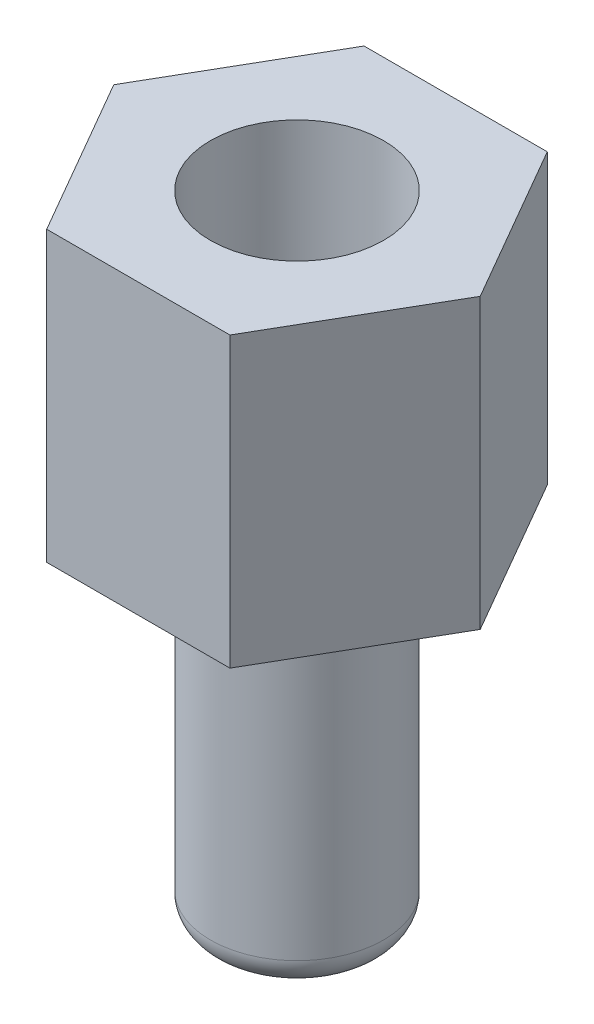
SolidWorks part; units mm, degrees
ref_plane "Front Plane" through (0, 0, 0) normal (0, 0, 1) x (1, 0, 0)
ref_plane "Top Plane" through (0, 0, 0) normal (0, 1, 0) x (1, 0, 0)
ref_plane "Right Plane" through (0, 0, 0) normal (1, 0, 0) x (0, 0, -1)
sketch "Sketch1" plane through (0, 0, 0) normal (0, 1, 0) x (1, 0, 0)
  line L1 (3.1754, 0) -> (1.5877, 2.75)
  line L2 (1.5877, 2.75) -> (-1.5877, 2.75)
  line L3 (-1.5877, 2.75) -> (-3.1754, 0)
  line L4 (-3.1754, 0) -> (-1.5877, -2.75)
  line L5 (-1.5877, -2.75) -> (1.5877, -2.75)
  line L6 (1.5877, -2.75) -> (3.1754, 0)
  circle A0 centre (0, 0) radius 2.75 construction
  point P1 (0, 0)
  dimension "D1" = 5.5
extrude "Boss-Extrude1" add sketch "Sketch1" along normal blind 5
sketch "Sketch2" plane through (0, 0, 0) normal (0, -1, 0) x (1, 0, 0)
  circle A0 centre (0, 0) radius 1.5
  dimension "D1" = 3
extrude "Boss-Extrude2" add sketch "Sketch2" along normal blind 6
fillet "Fillet1" radius 0.5 1 edges at (0, -6, -1.5)
sketch "Sketch3" plane through (0, 5, 0) normal (0, 1, 0) x (1, 0, 0)
  circle A0 centre (0, 0) radius 1.5
  dimension "D1" = 3
extrude "Cut-Extrude1" cut sketch "Sketch3" against normal blind 2.5
